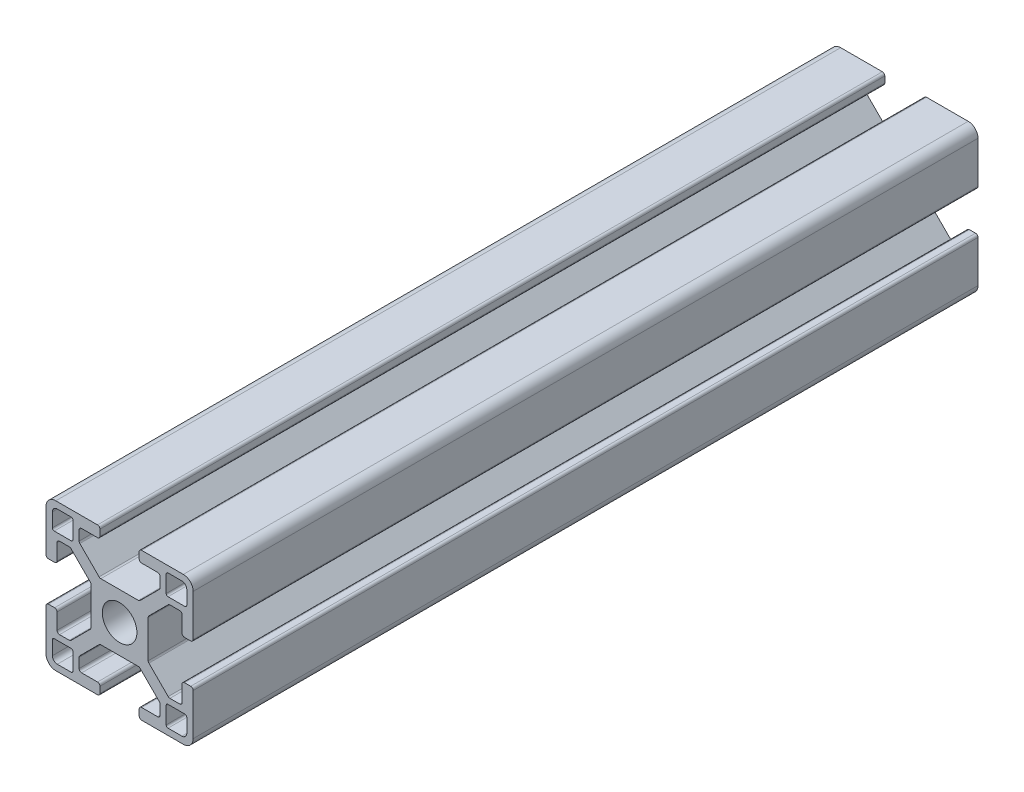
SolidWorks part; units mm, degrees
ref_plane "Front Plane" through (0, 0, 0) normal (0, 0, 1) x (1, 0, 0)
ref_plane "Top Plane" through (0, 0, 0) normal (0, 1, 0) x (1, 0, 0)
ref_plane "Right Plane" through (0, 0, 0) normal (1, 0, 0) x (0, 0, -1)
sketch "Sketch1" plane through (0, 0, 0) normal (0, 0, 1) x (1, 0, 0)
  line L0 (3.9799, -2.4733) -> (3.1981, -1.4942) construction
  line L1 (1.4942, -3.1981) -> (2.4733, -3.9799) construction
  line L2 (-2.4733, -3.9799) -> (-1.4942, -3.1981) construction
  line L3 (-3.1981, -1.4942) -> (-3.9799, -2.4733) construction
  line L4 (-3.9799, 2.4733) -> (-3.1981, 1.4942) construction
  line L5 (-1.4942, 3.1981) -> (-2.4733, 3.9799) construction
  line L6 (2.4733, 3.9799) -> (1.4942, 3.1981) construction
  line L7 (3.1981, 1.4942) -> (3.9799, 2.4733) construction
  line L8 (-12.6999, -13.6999) -> (-9.881, -13.6999)
  line L9 (-13.6999, -9.881) -> (-13.6999, -12.6999)
  line L10 (-9.88, -9.5) -> (-13.3189, -9.5)
  line L11 (-9.5, -13.3189) -> (-9.5, -9.88)
  line L12 (13.6999, -12.6999) -> (13.6999, -9.881)
  line L13 (9.881, -13.6999) -> (12.6999, -13.6999)
  line L14 (9.5, -9.88) -> (9.5, -13.3189)
  line L15 (13.3189, -9.5) -> (9.88, -9.5)
  line L16 (9.88, 9.5) -> (13.3189, 9.5)
  line L17 (9.5, 13.3189) -> (9.5, 9.88)
  line L18 (12.6999, 13.6999) -> (9.881, 13.6999)
  line L19 (13.6999, 9.881) -> (13.6999, 12.6999)
  line L20 (-13.6999, 12.6999) -> (-13.6999, 9.881)
  line L21 (-9.881, 13.6999) -> (-12.6999, 13.6999)
  line L22 (-9.5, 9.88) -> (-9.5, 13.3189)
  line L23 (-13.3189, 9.5) -> (-9.88, 9.5)
  line L24 (14.4999, -4) -> (13.2425, -4)
  line L25 (12.7425, -4.5) -> (12.7425, -7.7325)
  line L26 (12.2428, -8.25) -> (10.2602, -8.25)
  line L27 (9.9066, -8.1035) -> (5.9811, -4.178)
  line L28 (5.8347, -3.8245) -> (5.8347, -1.0125)
  line L29 (5.8347, -1.0125) -> (5.3247, -0.0625) construction
  line L30 (5.3247, -0.0625) -> (5.8347, 0.8875) construction
  line L31 (5.8347, 0.8875) -> (5.8347, 3.8245)
  line L32 (5.9811, 4.178) -> (9.9066, 8.1035)
  line L33 (10.2602, 8.25) -> (12.2428, 8.25)
  line L34 (12.7425, 7.7325) -> (12.7425, 4.5)
  line L35 (13.2425, 4) -> (14.4999, 4)
  line L36 (14.9999, 4.5) -> (14.9999, 12.9999)
  line L37 (12.9999, 14.9999) -> (4.5, 14.9999)
  line L38 (4, 14.4999) -> (4, 13.2425)
  line L39 (4.5, 12.7425) -> (7.7325, 12.7425)
  line L40 (8.25, 12.2428) -> (8.25, 10.2602)
  line L41 (8.1035, 9.9066) -> (4.178, 5.9811)
  line L42 (3.8245, 5.8347) -> (0.95, 5.8347)
  line L43 (0.95, 5.8347) -> (0, 5.3247) construction
  line L44 (0, 5.3247) -> (-0.95, 5.8347) construction
  line L45 (-0.95, 5.8347) -> (-3.8245, 5.8347)
  line L46 (-4.178, 5.9811) -> (-8.1035, 9.9066)
  line L47 (-8.25, 10.2602) -> (-8.25, 12.2428)
  line L48 (-7.7325, 12.7425) -> (-4.5, 12.7425)
  line L49 (-4, 13.2425) -> (-4, 14.4999)
  line L50 (-4.5, 14.9999) -> (-12.9999, 14.9999)
  line L51 (-14.9999, 12.9999) -> (-14.9999, 4.5)
  line L52 (-14.4999, 4) -> (-13.2425, 4)
  line L53 (-12.7425, 4.5) -> (-12.7425, 7.7325)
  line L54 (-12.2428, 8.25) -> (-10.2602, 8.25)
  line L55 (-9.9066, 8.1035) -> (-5.9811, 4.178)
  line L56 (-5.8347, 3.8245) -> (-5.8347, 0.8875)
  line L57 (-5.8347, 0.8875) -> (-5.3247, -0.0625) construction
  line L58 (-5.3247, -0.0625) -> (-5.8347, -1.0125) construction
  line L59 (-5.8347, -1.0125) -> (-5.8347, -3.8245)
  line L60 (-5.9811, -4.178) -> (-9.9066, -8.1035)
  line L61 (-10.2602, -8.25) -> (-12.2428, -8.25)
  line L62 (-12.7425, -7.7325) -> (-12.7425, -4.5)
  line L63 (-13.2425, -4) -> (-14.4999, -4)
  line L64 (-14.9999, -4.5) -> (-14.9999, -12.9999)
  line L65 (-12.9999, -14.9999) -> (-4.5, -14.9999)
  line L66 (-4, -14.4999) -> (-4, -13.2425)
  line L67 (-4.5, -12.7425) -> (-7.7325, -12.7425)
  line L68 (-8.25, -12.2428) -> (-8.25, -10.2602)
  line L69 (-8.1035, -9.9066) -> (-4.178, -5.9811)
  line L70 (-3.8245, -5.8347) -> (-0.95, -5.8347)
  line L71 (-0.95, -5.8347) -> (0, -5.3247) construction
  line L72 (0, -5.3247) -> (0.95, -5.8347) construction
  line L73 (0.95, -5.8347) -> (3.8245, -5.8347)
  line L74 (4.178, -5.9811) -> (8.1035, -9.9066)
  line L75 (8.25, -10.2602) -> (8.25, -12.2428)
  line L76 (7.7325, -12.7425) -> (4.5, -12.7425)
  line L77 (4, -13.2425) -> (4, -14.4999)
  line L78 (4.5, -14.9999) -> (12.9999, -14.9999)
  line L79 (14.9999, -12.9999) -> (14.9999, -4.5)
  line L80 (-5.8347, -1.0125) -> (-5.8347, 0.8875)
  line L81 (-0.95, 5.8347) -> (0.95, 5.8347)
  line L82 (5.8347, 0.8875) -> (5.8347, -1.0125)
  line L83 (-0.95, -5.8347) -> (0.95, -5.8347)
  arc A0 (2.4733, -3.9799) -> (3.9799, -2.4733) centre (3.1422, -3.1422) ccw construction
  arc A1 (-1.4942, -3.1981) -> (1.4942, -3.1981) centre (0, 0) ccw construction
  arc A2 (-3.9799, -2.4733) -> (-2.4733, -3.9799) centre (-3.1422, -3.1422) ccw construction
  arc A3 (-3.1981, 1.4942) -> (-3.1981, -1.4942) centre (0, 0) ccw construction
  arc A4 (-2.4733, 3.9799) -> (-3.9799, 2.4733) centre (-3.1422, 3.1422) ccw construction
  arc A5 (1.4942, 3.1981) -> (-1.4942, 3.1981) centre (0, 0) ccw construction
  arc A6 (3.9799, 2.4733) -> (2.4733, 3.9799) centre (3.1422, 3.1422) ccw construction
  arc A7 (3.1981, -1.4942) -> (3.1981, 1.4942) centre (0, 0) ccw construction
  arc A8 (-13.6999, -12.6999) -> (-12.6999, -13.6999) centre (-12.6999, -12.6999) ccw
  arc A9 (-13.3189, -9.5) -> (-13.6999, -9.881) centre (-13.3189, -9.881) ccw
  arc A10 (-9.5, -9.88) -> (-9.88, -9.5) centre (-9.88, -9.88) ccw
  arc A11 (-9.881, -13.6999) -> (-9.5, -13.3189) centre (-9.881, -13.3189) ccw
  arc A12 (12.6999, -13.6999) -> (13.6999, -12.6999) centre (12.6999, -12.6999) ccw
  arc A13 (9.5, -13.3189) -> (9.881, -13.6999) centre (9.881, -13.3189) ccw
  arc A14 (9.88, -9.5) -> (9.5, -9.88) centre (9.88, -9.88) ccw
  arc A15 (13.6999, -9.881) -> (13.3189, -9.5) centre (13.3189, -9.881) ccw
  arc A16 (9.5, 9.88) -> (9.88, 9.5) centre (9.88, 9.88) ccw
  arc A17 (9.881, 13.6999) -> (9.5, 13.3189) centre (9.881, 13.3189) ccw
  arc A18 (13.6999, 12.6999) -> (12.6999, 13.6999) centre (12.6999, 12.6999) ccw
  arc A19 (13.3189, 9.5) -> (13.6999, 9.881) centre (13.3189, 9.881) ccw
  arc A20 (14.9999, -4.5) -> (14.4999, -4) centre (14.4999, -4.5) ccw
  arc A21 (13.2425, -4) -> (12.7425, -4.5) centre (13.2425, -4.5) ccw
  arc A22 (12.2428, -8.25) -> (12.7425, -7.7325) centre (12.2428, -7.75) ccw
  arc A23 (9.9066, -8.1035) -> (10.2602, -8.25) centre (10.2602, -7.75) ccw
  arc A24 (5.8347, -3.8245) -> (5.9811, -4.178) centre (6.3347, -3.8245) ccw
  arc A25 (5.9811, 4.178) -> (5.8347, 3.8245) centre (6.3347, 3.8245) ccw
  arc A26 (10.2602, 8.25) -> (9.9066, 8.1035) centre (10.2602, 7.75) ccw
  arc A27 (12.7425, 7.7325) -> (12.2428, 8.25) centre (12.2428, 7.75) ccw
  arc A28 (12.7425, 4.5) -> (13.2425, 4) centre (13.2425, 4.5) ccw
  arc A29 (14.4999, 4) -> (14.9999, 4.5) centre (14.4999, 4.5) ccw
  arc A30 (14.9999, 12.9999) -> (12.9999, 14.9999) centre (12.9999, 12.9999) ccw
  arc A31 (4.5, 14.9999) -> (4, 14.4999) centre (4.5, 14.4999) ccw
  arc A32 (4, 13.2425) -> (4.5, 12.7425) centre (4.5, 13.2425) ccw
  arc A33 (8.25, 12.2428) -> (7.7325, 12.7425) centre (7.75, 12.2428) ccw
  arc A34 (8.1035, 9.9066) -> (8.25, 10.2602) centre (7.75, 10.2602) ccw
  arc A35 (3.8245, 5.8347) -> (4.178, 5.9811) centre (3.8245, 6.3347) ccw
  arc A36 (-4.178, 5.9811) -> (-3.8245, 5.8347) centre (-3.8245, 6.3347) ccw
  arc A37 (-8.25, 10.2602) -> (-8.1035, 9.9066) centre (-7.75, 10.2602) ccw
  arc A38 (-7.7325, 12.7425) -> (-8.25, 12.2428) centre (-7.75, 12.2428) ccw
  arc A39 (-4.5, 12.7425) -> (-4, 13.2425) centre (-4.5, 13.2425) ccw
  arc A40 (-4, 14.4999) -> (-4.5, 14.9999) centre (-4.5, 14.4999) ccw
  arc A41 (-12.9999, 14.9999) -> (-14.9999, 12.9999) centre (-12.9999, 12.9999) ccw
  arc A42 (-14.9999, 4.5) -> (-14.4999, 4) centre (-14.4999, 4.5) ccw
  arc A43 (-13.2425, 4) -> (-12.7425, 4.5) centre (-13.2425, 4.5) ccw
  arc A44 (-12.2428, 8.25) -> (-12.7425, 7.7325) centre (-12.2428, 7.75) ccw
  arc A45 (-9.9066, 8.1035) -> (-10.2602, 8.25) centre (-10.2602, 7.75) ccw
  arc A46 (-5.8347, 3.8245) -> (-5.9811, 4.178) centre (-6.3347, 3.8245) ccw
  arc A47 (-5.9811, -4.178) -> (-5.8347, -3.8245) centre (-6.3347, -3.8245) ccw
  arc A48 (-10.2602, -8.25) -> (-9.9066, -8.1035) centre (-10.2602, -7.75) ccw
  arc A49 (-12.7425, -7.7325) -> (-12.2428, -8.25) centre (-12.2428, -7.75) ccw
  arc A50 (-12.7425, -4.5) -> (-13.2425, -4) centre (-13.2425, -4.5) ccw
  arc A51 (-14.4999, -4) -> (-14.9999, -4.5) centre (-14.4999, -4.5) ccw
  arc A52 (-14.9999, -12.9999) -> (-12.9999, -14.9999) centre (-12.9999, -12.9999) ccw
  arc A53 (-4.5, -14.9999) -> (-4, -14.4999) centre (-4.5, -14.4999) ccw
  arc A54 (-4, -13.2425) -> (-4.5, -12.7425) centre (-4.5, -13.2425) ccw
  arc A55 (-8.25, -12.2428) -> (-7.7325, -12.7425) centre (-7.75, -12.2428) ccw
  arc A56 (-8.1035, -9.9066) -> (-8.25, -10.2602) centre (-7.75, -10.2602) ccw
  arc A57 (-3.8245, -5.8347) -> (-4.178, -5.9811) centre (-3.8245, -6.3347) ccw
  arc A58 (4.178, -5.9811) -> (3.8245, -5.8347) centre (3.8245, -6.3347) ccw
  arc A59 (8.25, -10.2602) -> (8.1035, -9.9066) centre (7.75, -10.2602) ccw
  arc A60 (7.7325, -12.7425) -> (8.25, -12.2428) centre (7.75, -12.2428) ccw
  arc A61 (4.5, -12.7425) -> (4, -13.2425) centre (4.5, -13.2425) ccw
  arc A62 (4, -14.4999) -> (4.5, -14.9999) centre (4.5, -14.4999) ccw
  arc A63 (12.9999, -14.9999) -> (14.9999, -12.9999) centre (12.9999, -12.9999) ccw
  arc A64 (-12.6999, 13.6999) -> (-13.6999, 12.6999) centre (-12.6999, 12.6999) ccw
  arc A65 (-9.5, 13.3189) -> (-9.881, 13.6999) centre (-9.881, 13.3189) ccw
  arc A66 (-9.88, 9.5) -> (-9.5, 9.88) centre (-9.88, 9.88) ccw
  arc A67 (-13.6999, 9.881) -> (-13.3189, 9.5) centre (-13.3189, 9.881) ccw
  circle A68 centre (0, 0) radius 3.53
extrude "Boss-Extrude1" add sketch "Sketch1" along normal mid plane 160
